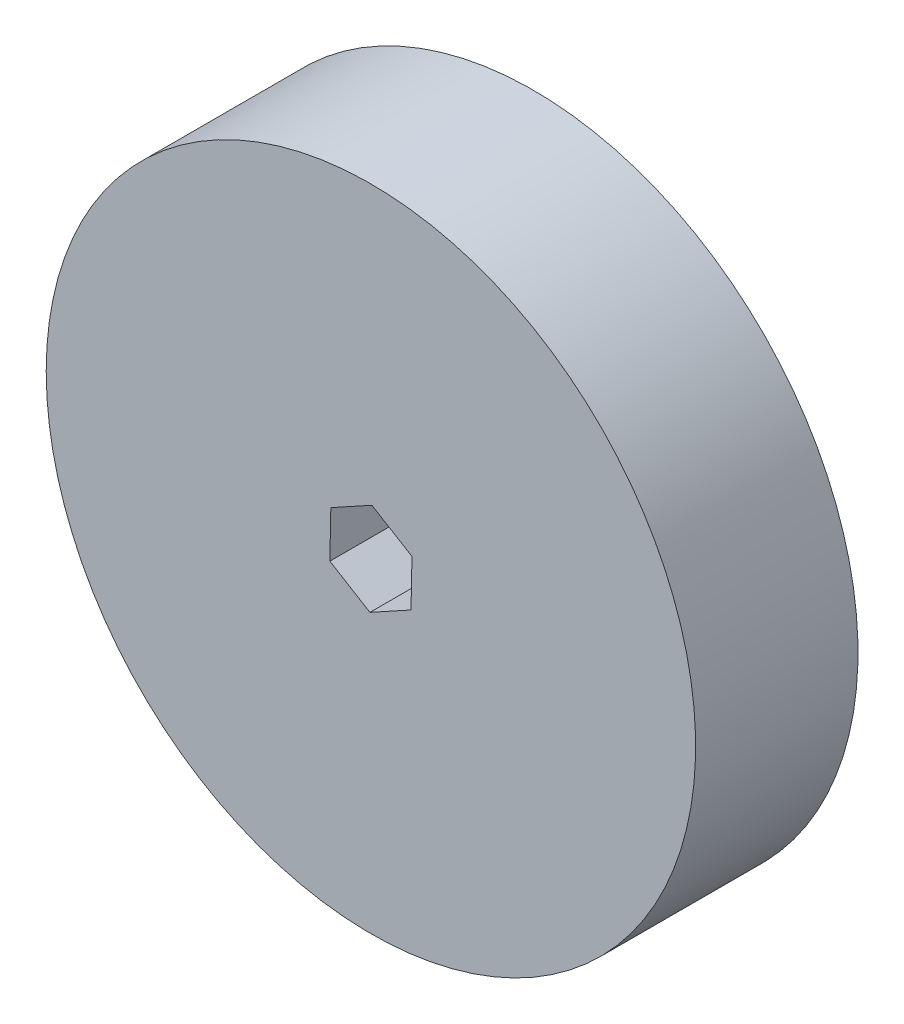
SolidWorks part; units mm, degrees
ref_plane "Front Plane" through (0, 0, 0) normal (0, 0, 1) x (1, 0, 0)
ref_plane "Top Plane" through (0, 0, 0) normal (0, 1, 0) x (1, 0, 0)
ref_plane "Right Plane" through (0, 0, 0) normal (1, 0, 0) x (0, 0, -1)
sketch "Sketch1" plane through (0, 0, 0) normal (0, 0, 1) x (1, 0, 0)
  line L1 (4.8185, 2.6502) -> (0.1141, 5.4981)
  line L2 (0.1141, 5.4981) -> (-4.7044, 2.8479)
  line L3 (-4.7044, 2.8479) -> (-4.8185, -2.6502)
  line L4 (-4.8185, -2.6502) -> (-0.1141, -5.4981)
  line L5 (-0.1141, -5.4981) -> (4.7044, -2.8479)
  line L6 (4.7044, -2.8479) -> (4.8185, 2.6502)
  circle A0 centre (0, 0) radius 38.1
  circle A1 centre (0, 0) radius 4.7625 construction
  dimension "D1" = 76.2
  dimension "D2" = 9.525
extrude "Boss-Extrude1" add sketch "Sketch1" along normal blind 19.05
